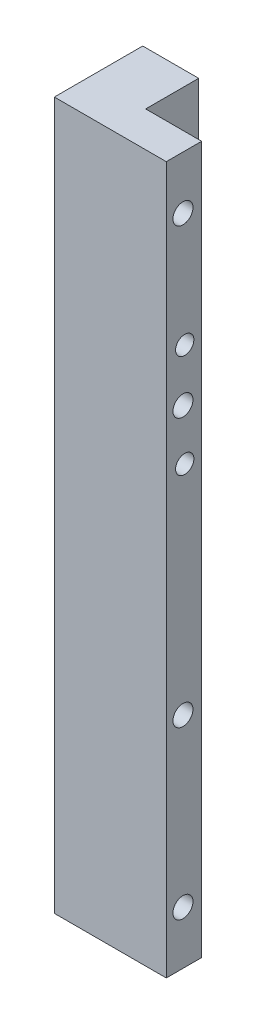
SolidWorks part; units mm, degrees
ref_plane "Front Plane" through (0, 0, 0) normal (0, 0, 1) x (1, 0, 0)
ref_plane "Top Plane" through (0, 0, 0) normal (0, 1, 0) x (1, 0, 0)
ref_plane "Right Plane" through (0, 0, 0) normal (1, 0, 0) x (0, 0, -1)
sketch "Sketch1" plane through (0, 0, 0) normal (0, 1, 0) x (1, 0, 0)
  line L0 (0, -55) -> (0, 55) construction
  line L1 (-9.5, -3) -> (9.5, -3)
  line L2 (-9.5, -3) -> (-9.5, 3)
  line L3 (-9.5, 3) -> (9.5, 3)
  line L4 (9.5, -3) -> (9.5, 3)
  line L5 (-9.5, -3) -> (9.5, 3) construction
  line L6 (-9.5, 3) -> (9.5, -3) construction
  line L7 (-9.5, 3) -> (0, 3)
  line L8 (-9.5, 3) -> (-9.5, 12)
  line L9 (-9.5, 12) -> (0, 12)
  line L10 (0, 3) -> (0, 12)
  point P0 (0, 0)
  dimension "D1" = 6
  dimension "D2" = 19
  dimension "D3" = 9
  dimension "D4" = 9.5
extrude "Boss-Extrude1" add sketch "Sketch1" along normal blind 120
sketch "Sketch2" plane through (9.5, 0, -9.5) normal (-1, 0, 0) x (0, 0, 1)
  line L0 (9.5, 0) -> (9.5, 120)
  line L2 (34.1, 19.5) -> (9.5, 19.5)
  line L3 (34.1, 54.75) -> (9.5, 54.75)
  line L4 (34.1, 65.25) -> (9.5, 65.25)
  line L5 (34.1, 100.5) -> (9.5, 100.5)
  line L6 (34.1, 60) -> (9.5, 60)
  line L16 (34.1, 120) -> (-22.7, 120)
  line L17 (-22.7, 120) -> (-22.7, 0)
  line L18 (-22.7, 0) -> (34.1, 0)
  line L19 (34.1, 0) -> (34.1, 120)
  circle A0 centre (9.5, 24) radius 1.7
  circle A1 centre (9.5, 50.25) radius 1.7
  circle A2 centre (9.5, 69.75) radius 1.7
  circle A3 centre (9.5, 96) radius 1.7
  circle A4 centre (9.6709, 111) radius 1.7
  circle A5 centre (9.6709, 82.75) radius 1.7
  circle A6 centre (9.6709, 37.25) radius 1.7
  circle A7 centre (9.6709, 9) radius 1.7
  circle A8 centre (9.3709, 91.5) radius 1.55
  circle A9 centre (9.3709, 74) radius 1.55
  dimension "D1" = 3.4
  dimension "D3" = 3.4
  dimension "D2" = 4.5
  dimension "D4" = 4.5
extrude "Cut-Extrude1" cut sketch "Sketch2" along normal blind 19 contours A4 L0 | A4 L0 | A5 L0 | A5 L0 | A6 L0 | A6 L0 | A7 L0 | A7 L0 | A8 L0 | A8 L0 | A9 L0 | A9 L0 | A3 | A0 | A2 | A1
